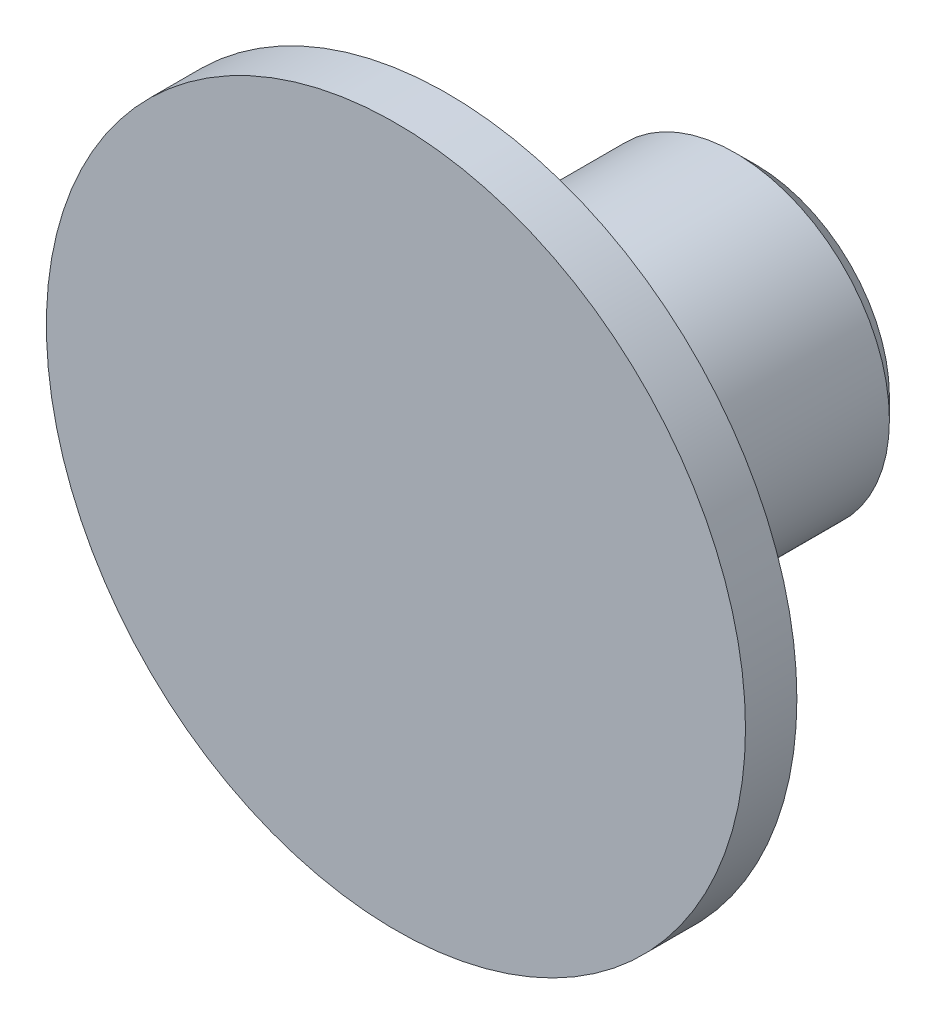
SolidWorks part; units mm, degrees
ref_plane "前视基准面" through (0, 0, 0) normal (0, 0, 1) x (1, 0, 0)
ref_plane "上视基准面" through (0, 0, 0) normal (0, 1, 0) x (1, 0, 0)
ref_plane "右视基准面" through (0, 0, 0) normal (1, 0, 0) x (0, 0, -1)
sketch "草图1" plane through (0, 0, 0) normal (0, 0, 1) x (1, 0, 0)
  circle A0 centre (0, 0) radius 15
  dimension "D1" = 30
extrude "凸台-拉伸1" add sketch "草图1" along normal blind 30
cosmetic thread "装饰螺纹线2" parameters "D1"=10, "D2"=27.835
sketch "草图2" plane through (0, 0, 30) normal (0, 0, 1) x (1, 0, 0)
  circle A0 centre (0, 0) radius 34
  dimension "D1" = 68
extrude "凸台-拉伸2" add sketch "草图2" along normal blind 5
chamfer "倒角1" distance 2 angle 45 1 edges at (15, 0, 0)
